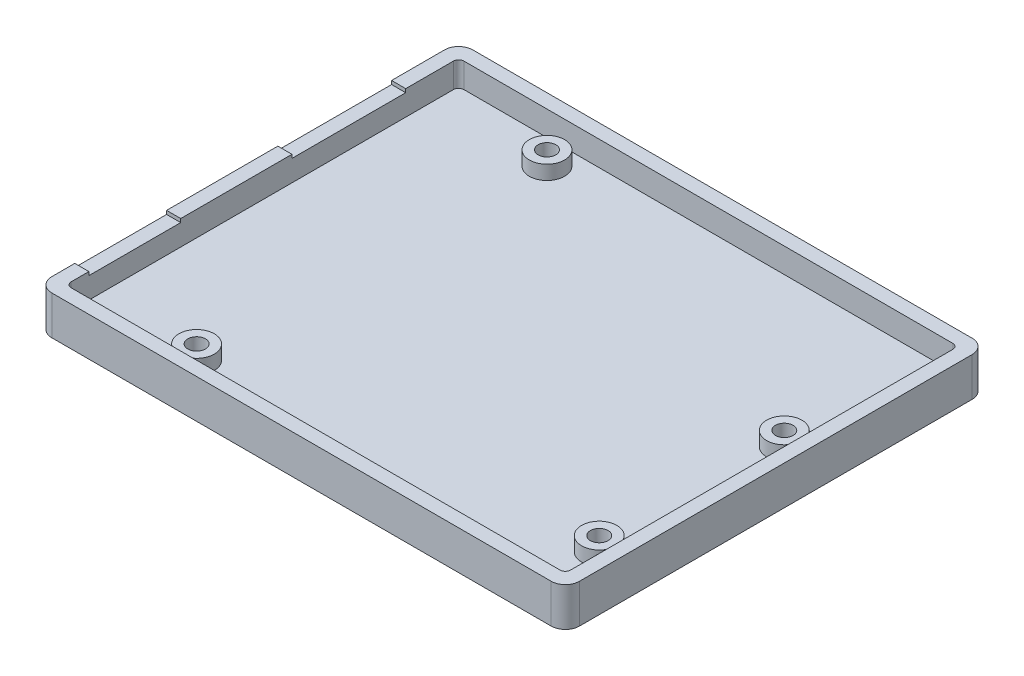
SolidWorks part; units mm, degrees
ref_plane "Front Plane" through (0, 0, 0) normal (0, 0, 1) x (1, 0, 0)
ref_plane "Top Plane" through (0, 0, 0) normal (0, 1, 0) x (1, 0, 0)
ref_plane "Right Plane" through (0, 0, 0) normal (1, 0, 0) x (0, 0, -1)
sketch "Board Outline" plane through (0, 0, 0) normal (0, 1, 0) x (1, 0, 0)
  line L1 (0, 0) -> (68.7, 0)
  line L2 (0, 0) -> (0, 53.6)
  line L3 (0, 53.6) -> (68.7, 53.6)
  line L4 (68.7, 0) -> (68.7, 53.6)
  dimension "D1" = 68.7
  dimension "D2" = 53.6
sketch "Sketch2" plane through (0, 0, 0) normal (0, 1, 0) x (1, 0, 0)
  line L8 (-3, 56.6) -> (-3, -3)
  line L9 (-3, -3) -> (71.7, -3)
  line L10 (71.7, -3) -> (71.7, 56.6)
  line L11 (71.7, 56.6) -> (-3, 56.6)
  line L12 (-3, 56.6) -> (-3, -3)
  line L13 (-3, -3) -> (71.7, -3)
  line L14 (71.7, -3) -> (71.7, 56.6)
  line L15 (71.7, 56.6) -> (-3, 56.6)
  dimension "D1" = 3
extrude "Boss-Extrude1" add sketch "Sketch2" against normal blind 2 from offset 2 offset against normal yes
sketch "Sketch3" plane through (0, 0, 0) normal (0, 1, 0) x (1, 0, 0)
  line L0 (69.7, 54.6) -> (-1, 54.6)
  line L1 (-1, 54.6) -> (-1, -1)
  line L2 (-1, -1) -> (69.7, -1)
  line L3 (69.7, -1) -> (69.7, 54.6)
  line L4 (71.7, 56.6) -> (-3, 56.6)
  line L5 (-3, 56.6) -> (-3, -3)
  line L6 (-3, -3) -> (71.7, -3)
  line L7 (71.7, -3) -> (71.7, 56.6)
  line L8 (71.7, 56.6) -> (-3, 56.6)
  line L9 (-3, 56.6) -> (-3, -3)
  line L10 (-3, -3) -> (71.7, -3)
  line L11 (71.7, -3) -> (71.7, 56.6)
  dimension "D1" = 0
  dimension "D2" = 2
extrude "Boss-Extrude2" add sketch "Sketch3" along normal offset from surface (3.5 mm away) 1.5 from surface at -2 up to plane "Top Plane" offset beyond the face yes starting at face at (34.35, -2, -26.8)
sketch "Sketch4" plane through (0, 0, 0) normal (0, 1, 0) x (1, 0, 0)
  circle A1 centre (14, 2.5) radius 2.5
  circle A5 centre (15, 51.1) radius 2.5
  circle A6 centre (66.2, 33.5) radius 2.5
  circle A7 centre (66, 7.5) radius 2.5
  point P3 (0, 0)
  point P5 (0, 0)
  dimension "D1" = 5
  dimension "D2" = 14
  dimension "D3" = 15
  dimension "D4" = 66
  dimension "D5" = 66.2
  dimension "D6" = 2.5
  dimension "D7" = 7.5
  dimension "D8" = 33.5
  dimension "D9" = 51.1
extrude "Boss-Extrude3" add sketch "Sketch4" along normal up to surface (4 mm away) from surface at -4 contours A1
hole_wizard "M3x0.5 Tapped Hole2" positions "3DSketch8" profile "Sketch14" tap size "M3x0.5" standard "ANSI Metric"
sketch3d "3DSketch8"
  line L0 (66, 0, -7.5) -> (66, -2, -7.5) construction
  line L1 (66.2, 0, -33.5) -> (66.2, -2, -33.5) construction
  line L2 (15, 0, -51.1) -> (15, -2, -51.1) construction
  line L3 (14, 0, -2.5) -> (14, -2, -2.5) construction
  point P0 (66, 0, -7.5)
  point P4 (66.2, 0, -33.5)
  point P8 (15, 0, -51.1)
  point P12 (14, 0, -2.5)
sketch "Sketch14" plane through (66, 0, -7.5) normal (1, 0, 0) x (0, 0, 1)
  line L0 (0, 0) -> (0, 3.2511)
  line L1 (0, 3.2511) -> (1.25, 2.5)
  line L2 (1.25, 2.5) -> (1.25, 0)
  line L5 (1.25, 0) -> (0, 0)
  line L10 (0, 3.2511) -> (-1.25, 2.5) construction
  line L11 (0, -6.35) -> (0, 107.95) construction
  dimension "Tap Drill Dia." = 2.5
  dimension "Tap Drill Depth" = 2.5
  dimension "Drill Angle" = 118
cosmetic thread "Hole Thread5" parameters "D1"=2, "D2"=3
cosmetic thread "Hole Thread6" parameters "D1"=2, "D2"=3
cosmetic thread "Hole Thread7" parameters "D1"=2, "D2"=3
cosmetic thread "Hole Thread8" parameters "D1"=2, "D2"=3
fillet "Fillet1" radius 0.75 4 edges at (-1, -0.25, -54.6) (69.7, -0.25, -54.6) (-1, -0.25, 1) (69.7, -0.25, 1)
fillet "Fillet2" radius 2 4 edges at (-3, -1.25, -56.6) (71.7, -1.25, 3) (71.7, -1.25, -56.6) (-3, -1.25, 3)
sketch "Sketch15" plane through (0, 1.5, 0) normal (0, 1, 0) x (1, 0, 0)
  line L24 (-1, 15.25) -> (-3, 15.25)
  line L25 (-1, 2.25) -> (-1, 15.25)
  line L26 (-3, 2.25) -> (-1, 2.25)
  line L27 (-3, 15.25) -> (-3, 2.25)
  line L32 (-1, 47.1) -> (-3, 47.1)
  line L33 (-1, 31) -> (-1, 47.1)
  line L34 (-3, 31) -> (-1, 31)
  line L35 (-3, 47.1) -> (-3, 31)
extrude "Cut-Extrude1" cut sketch "Sketch15" against normal blind 0.5
